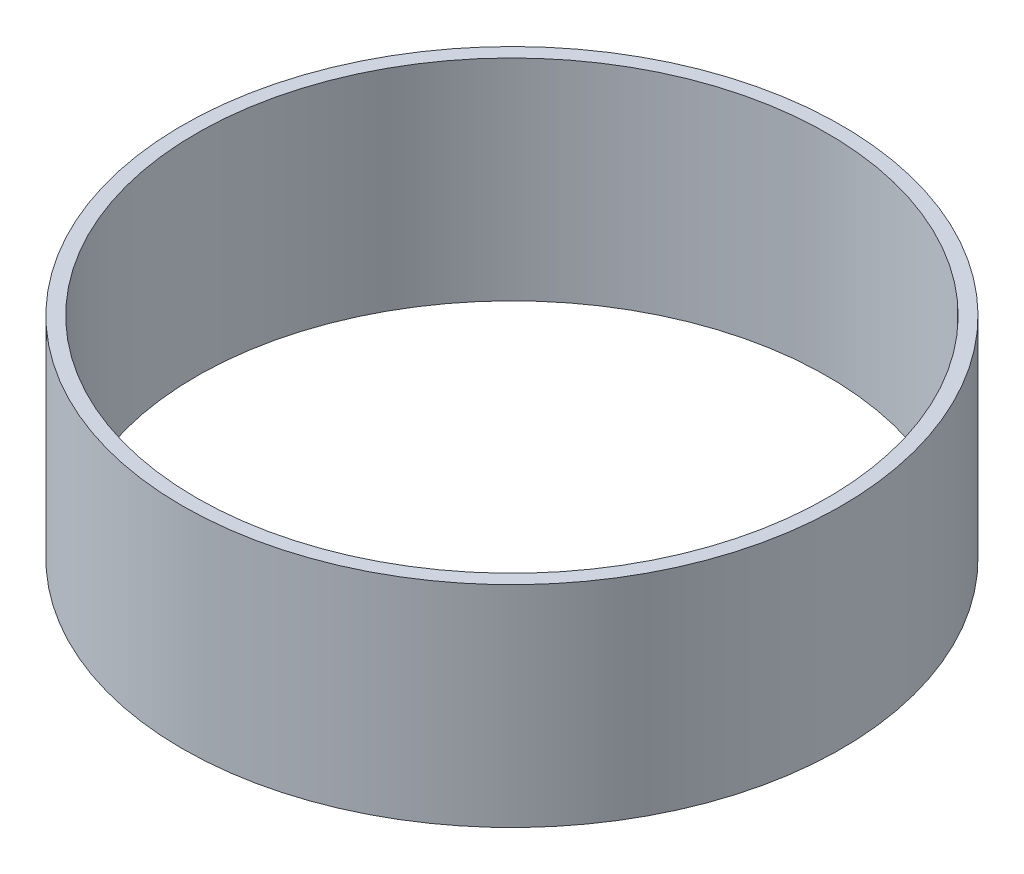
SolidWorks part; units mm, degrees
ref_plane "Front Plane" through (0, 0, 0) normal (0, 0, 1) x (1, 0, 0)
ref_plane "Top Plane" through (0, 0, 0) normal (0, 1, 0) x (1, 0, 0)
ref_plane "Right Plane" through (0, 0, 0) normal (1, 0, 0) x (0, 0, -1)
sketch "Sketch3" plane through (0, 0, 0) normal (0, 1, 0) x (1, 0, 0)
  circle A0 centre (0, 0) radius 22.5044
  circle A1 centre (0, 0) radius 23.5044
  dimension "D1" = 1
extrude "Boss-Extrude2" add sketch "Sketch3" along normal blind 15
